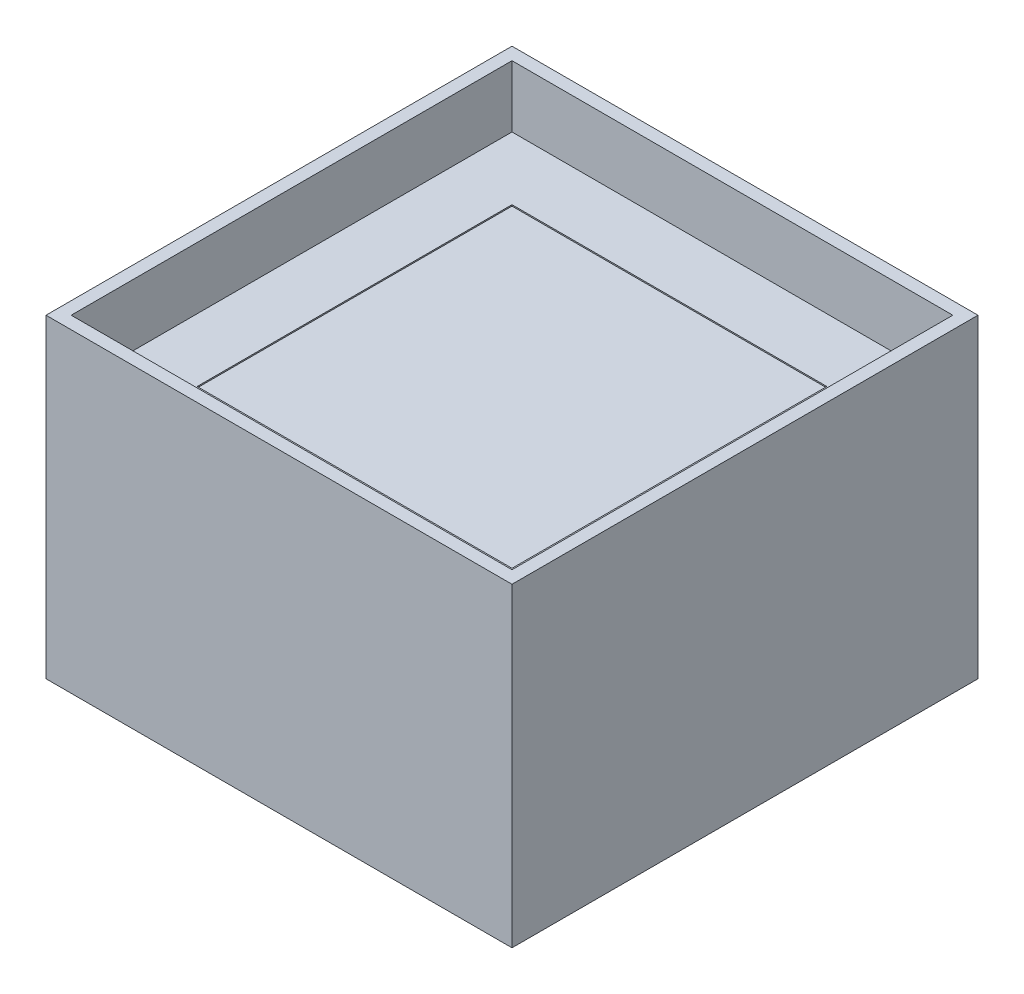
SolidWorks part; units mm, degrees
ref_plane "前视基准面" through (0, 0, 0) normal (0, 0, 1) x (1, 0, 0)
ref_plane "上视基准面" through (0, 0, 0) normal (0, 1, 0) x (1, 0, 0)
ref_plane "右视基准面" through (0, 0, 0) normal (1, 0, 0) x (0, 0, -1)
sketch "草图1" plane through (0, 0, 0) normal (0, 1, 0) x (1, 0, 0)
  line L1 (-175, 175) -> (175, 175)
  line L2 (-175, 175) -> (-175, -175)
  line L3 (-175, -175) -> (175, -175)
  line L4 (175, 175) -> (175, -175)
  line L5 (-175, 175) -> (175, -175) construction
  line L6 (-175, -175) -> (175, 175) construction
  line L7 (-185, 185) -> (185, 185)
  line L8 (-185, 185) -> (-185, -185)
  line L9 (-185, -185) -> (185, -185)
  line L10 (185, 185) -> (185, -185)
  line L11 (-185, 185) -> (185, -185) construction
  line L12 (-185, -185) -> (185, 185) construction
  point P0 (0, 0)
  point P6 (0, 0)
  dimension "D1" = 350
  dimension "D2" = 10
extrude "凸台-拉伸1" add sketch "草图1" along normal blind 50
sketch "草图2" plane through (0, 0, 0) normal (0, -1, 0) x (1, 0, 0)
  line L1 (-185, 185) -> (185, 185)
  line L2 (-185, 185) -> (-185, -185)
  line L3 (-185, -185) -> (185, -185)
  line L4 (185, 185) -> (185, -185)
extrude "凸台-拉伸2" add sketch "草图2" along normal blind 200
sketch "草图3" plane through (0, 0, 0) normal (0, 1, 0) x (1, 0, 0)
  line L0 (175, 175) -> (-175, 175) construction
  line L1 (-125, 125) -> (125, 125)
  line L2 (-125, 125) -> (-125, -125)
  line L3 (-125, -125) -> (125, -125)
  line L4 (125, 125) -> (125, -125)
  line L5 (-125, 125) -> (125, -125) construction
  line L6 (-125, -125) -> (125, 125) construction
  line L7 (175, -175) -> (175, 175) construction
  line L9 (-175, 175) -> (175, 175)
  line L10 (-175, 175) -> (-175, -175)
  line L11 (-175, -175) -> (175, -175)
  line L12 (175, 175) -> (175, -175)
  point P0 (0, 0)
  dimension "D1" = 50
  dimension "D2" = 50
extrude "凸台-拉伸3" add sketch "草图3" along normal blind 1
